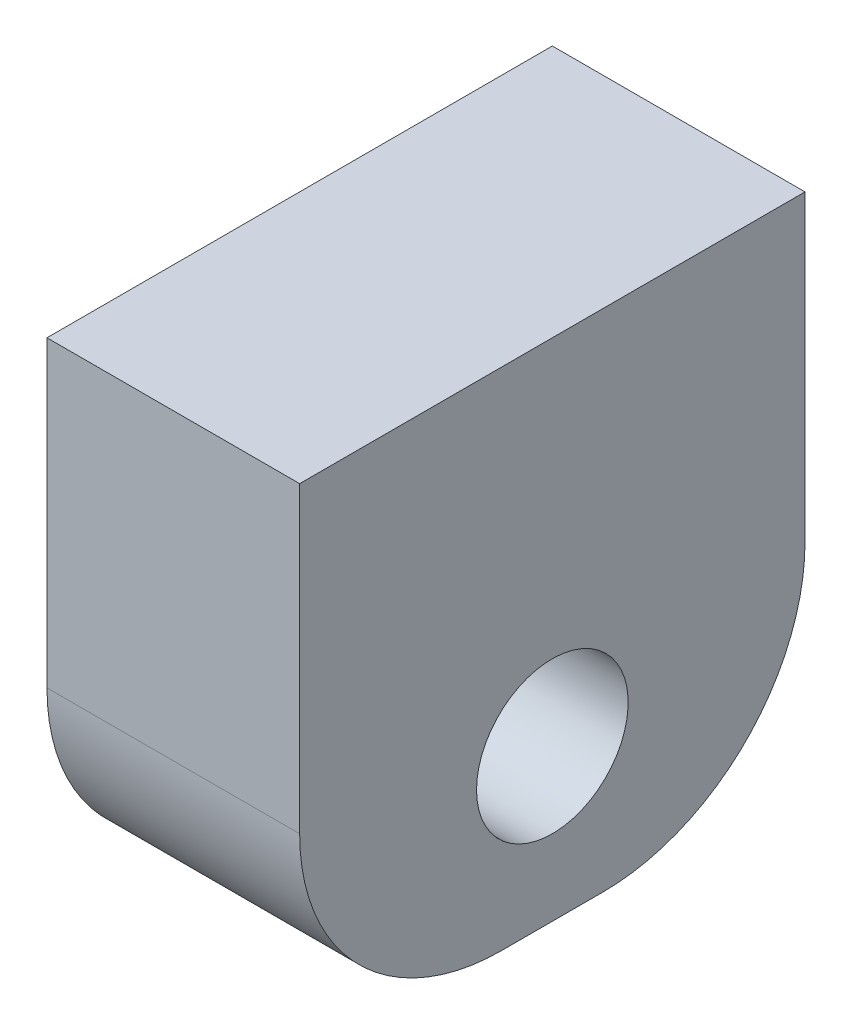
SolidWorks part; units mm, degrees
ref_plane "Front Plane" through (0, 0, 0) normal (0, 0, 1) x (1, 0, 0)
ref_plane "Top Plane" through (0, 0, 0) normal (0, 1, 0) x (1, 0, 0)
ref_plane "Right Plane" through (0, 0, 0) normal (1, 0, 0) x (0, 0, -1)
sketch "Sketch1" plane through (0, 0, 0) normal (0, 0, 1) x (1, 0, 0)
  line L1 (0, 0) -> (5, 0)
  line L2 (0, 0) -> (0, 10)
  line L3 (0, 10) -> (5, 10)
  line L4 (5, 0) -> (5, 10)
  dimension "D1" = 5
  dimension "D2" = 10
extrude "Boss-Extrude1" add sketch "Sketch1" along normal blind 10
sketch "Sketch2" plane through (0, 0, 0) normal (-1, 0, 0) x (0, 0, 1)
  line L0 (10, 0) -> (0, 0) construction
  circle A0 centre (5, 3) radius 1.5
  point P4 (5, 0)
  dimension "D1" = 3
  dimension "D3" = 3
  dimension "D2" = 0
extrude "Cut-Extrude1" cut sketch "Sketch2" against normal through all
fillet "Fillet1" radius 4 2 edges at (2.5, 0, 0) (2.5, 0, 10)
